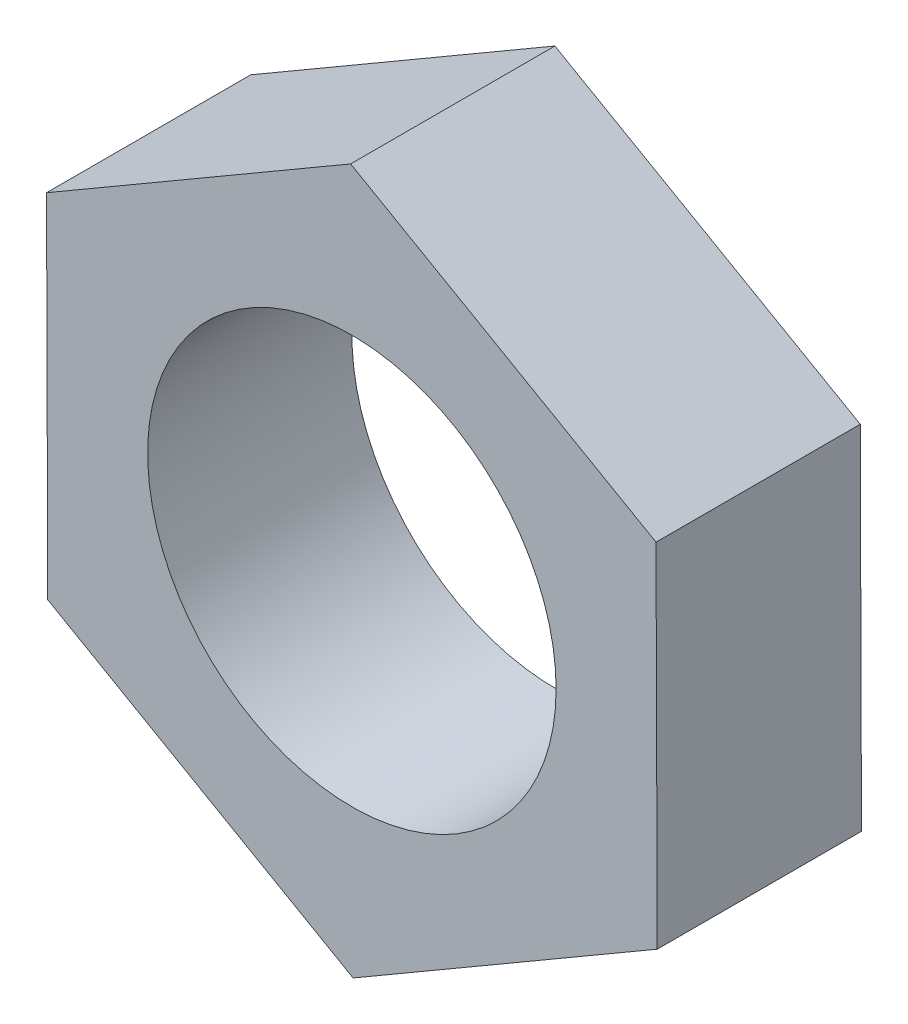
SolidWorks part; units mm, degrees
ref_plane "Front Plane" through (0, 0, 0) normal (0, 0, 1) x (1, 0, 0)
ref_plane "Top Plane" through (0, 0, 0) normal (0, 1, 0) x (1, 0, 0)
ref_plane "Right Plane" through (0, 0, 0) normal (1, 0, 0) x (0, 0, -1)
sketch "Sketch1" plane through (0, 0, 0) normal (0, 0, 1) x (1, 0, 0)
  line L1 (1.8689, -1.0704) -> (1.8614, 1.0833)
  line L2 (1.8614, 1.0833) -> (-0.0075, 2.1537)
  line L3 (-0.0075, 2.1537) -> (-1.8689, 1.0704)
  line L4 (-1.8689, 1.0704) -> (-1.8614, -1.0833)
  line L5 (-1.8614, -1.0833) -> (0.0075, -2.1537)
  line L6 (0.0075, -2.1537) -> (1.8689, -1.0704)
  circle A0 centre (0, 0) radius 1.25
  circle A1 centre (0, 0) radius 1.8652 construction
  dimension "D1" = 2.5
extrude "Boss-Extrude1" add sketch "Sketch1" along normal blind 1.25
scale "Scale1" scale about centroid uniform scaling yes scale factor 1.5
